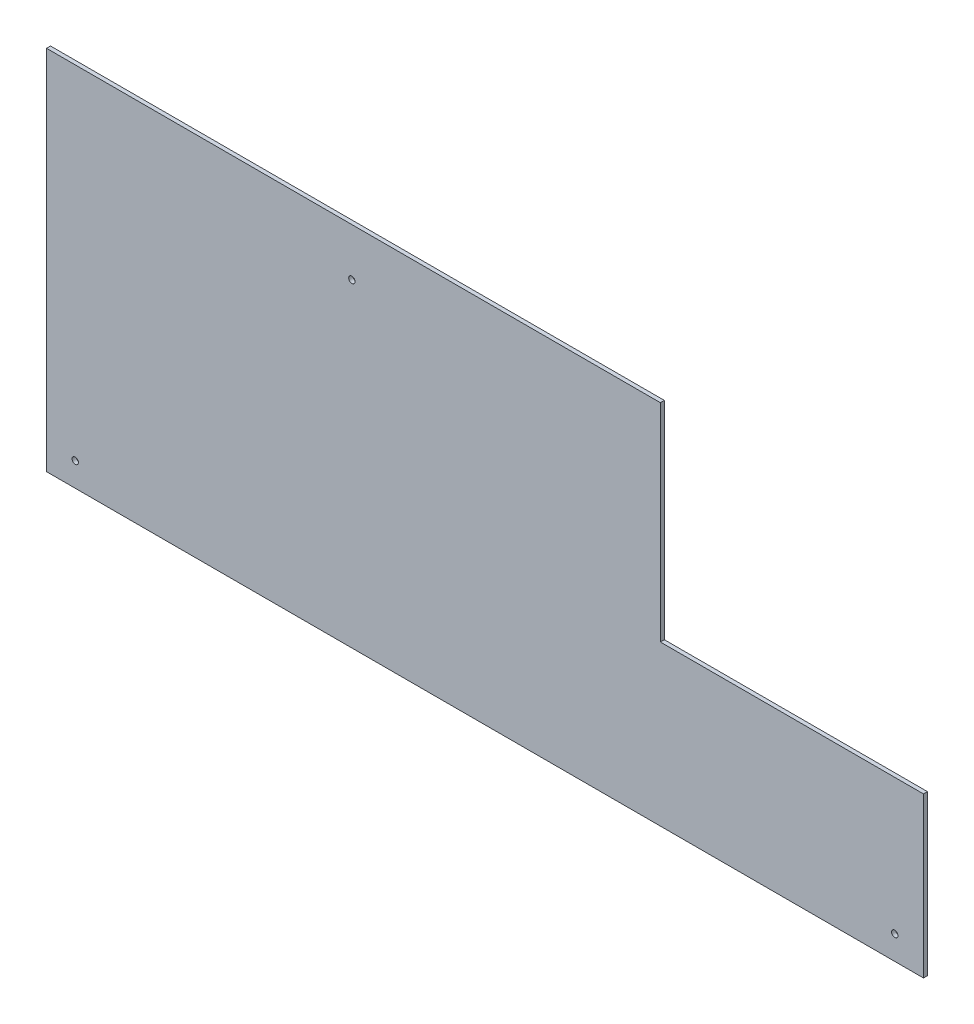
SolidWorks part; units mm, degrees
material "Acrilico (impatto medio-alto)"
ref_plane "Piano frontale" through (0, 0, 0) normal (0, 0, 1) x (1, 0, 0)
ref_plane "Piano superiore" through (0, 0, 0) normal (0, 1, 0) x (1, 0, 0)
ref_plane "Piano destro" through (0, 0, 0) normal (1, 0, 0) x (0, 0, -1)
sketch "Schizzo1" plane through (0, 0, 0) normal (0, 0, 1) x (1, 0, 0)
  line L1 (275, -115) -> (-275, -115)
  line L2 (275, -115) -> (275, 115)
  line L3 (275, 115) -> (-275, 115)
  line L4 (-275, -115) -> (-275, 115)
  line L5 (275, -115) -> (-275, 115) construction
  line L6 (275, 115) -> (-275, -115) construction
  point P4 (0, 0)
  dimension "D1" = 230
  dimension "D2" = 550
extrude "Estrusione-Estrusione1" add sketch "Schizzo1" along normal blind 2.5
sketch "Schizzo2" plane through (0, 0, 0) normal (0, 0, -1) x (-1, 0, 0)
  line L1 (-275, 115) -> (-110, 115)
  line L2 (-275, 115) -> (-275, -15)
  line L3 (-275, -15) -> (-110, -15)
  line L4 (-110, 115) -> (-110, -15)
  line L5 (-275, 115) -> (-110, -15) construction
  line L6 (-275, -15) -> (-110, 115) construction
  line L8 (-275, 115) -> (275, 115) construction
  line L9 (-275, -115) -> (-275, 115) construction
  point P4 (-192.5, 50)
  dimension "D1" = 130
  dimension "D3" = 165
extrude "Taglio-Estrusione1" cut sketch "Schizzo2" against normal blind 10
sketch "Schizzo3" plane through (0, 0, 2.5) normal (0, 0, 1) x (1, 0, 0)
  line L0 (-257, -100) -> (257, -100) construction
  line L1 (275, -115) -> (-275, -115) construction
  line L2 (275, 115) -> (275, -115) construction
  line L3 (-275, 115) -> (-275, -110) construction
  circle A0 centre (-83.5, 85) radius 2
  circle A1 centre (-257, -100) radius 2
  circle A2 centre (257, -100) radius 2
  dimension "D1" = 4
  dimension "D4" = 18
  dimension "D2" = 15
  dimension "D3" = 18
extrude "Taglio-Estrusione2" cut sketch "Schizzo3" against normal blind 10
